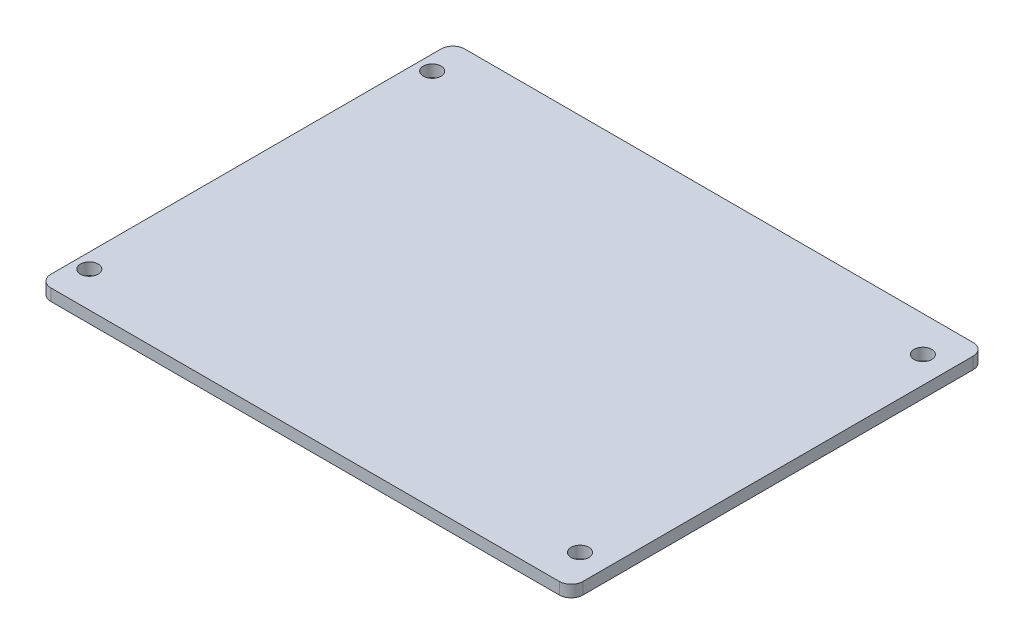
SolidWorks part; units mm, degrees
ref_plane "Alzado" through (0, 0, 0) normal (0, 0, 1) x (1, 0, 0)
ref_plane "Planta" through (0, 0, 0) normal (0, 1, 0) x (1, 0, 0)
ref_plane "Vista lateral" through (0, 0, 0) normal (1, 0, 0) x (0, 0, -1)
sketch "Croquis1" plane through (0, 0, 0) normal (0, 1, 0) x (1, 0, 0)
  line L1 (-45, 35) -> (45, 35)
  line L2 (-45, 35) -> (-45, -35)
  line L3 (-45, -35) -> (45, -35)
  line L4 (45, 35) -> (45, -35)
  circle A0 centre (-42.5, -29) radius 1.5
  circle A1 centre (-42.5, 29) radius 1.5
  circle A2 centre (40.5, -29) radius 1.5
  circle A3 centre (40.5, 29) radius 1.5
  point P4 (0, 35)
  point P6 (45, 0)
  dimension "D3" = 3
  dimension "D4" = 3
  dimension "D9" = 3
  dimension "D10" = 3
  dimension "D1" = 70
  dimension "D2" = 90
  dimension "D5" = 2.5
  dimension "D6" = 2.5
  dimension "D7" = 6
  dimension "D8" = 6
  dimension "D11" = 6
  dimension "D12" = 6
  dimension "D13" = 4.5
  dimension "D14" = 4.5
extrude "Saliente-Extruir1" add sketch "Croquis1" along normal blind 2
fillet "Redondeo1" radius 2 4 edges at (-45, 1, 35) (-45, 1, -35) (45, 1, -35) (45, 1, 35)
